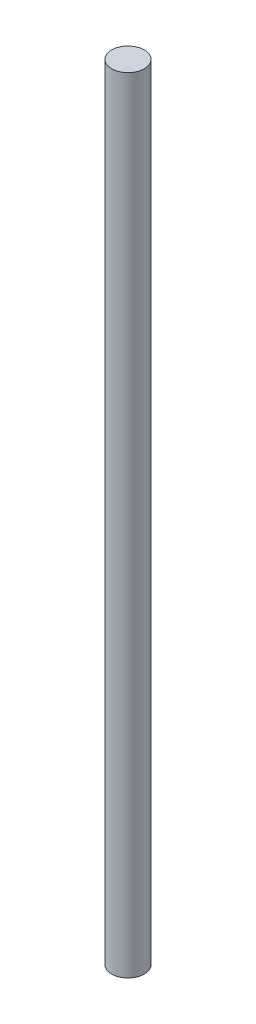
SolidWorks part; units mm, degrees
ref_plane "Front Plane" through (0, 0, 0) normal (0, 0, 1) x (1, 0, 0)
ref_plane "Top Plane" through (0, 0, 0) normal (0, 1, 0) x (1, 0, 0)
ref_plane "Right Plane" through (0, 0, 0) normal (1, 0, 0) x (0, 0, -1)
sketch "Sketch1" plane through (0, 0, 0) normal (0, 1, 0) x (1, 0, 0)
  circle A0 centre (0, 0) radius 12.5
  dimension "D1" = 25
extrude "Boss-Extrude1" add sketch "Sketch1" along normal mid plane 600
equation "\"a\"= 1"
equation "\"b\"= 1"
equation "\"c\"= 1"
equation "\"d\"= 1"
equation "\"e\"= 1"
equation "\"x\"= 1"
equation "\"y\"= 1"
equation "\"z\"= 1"
